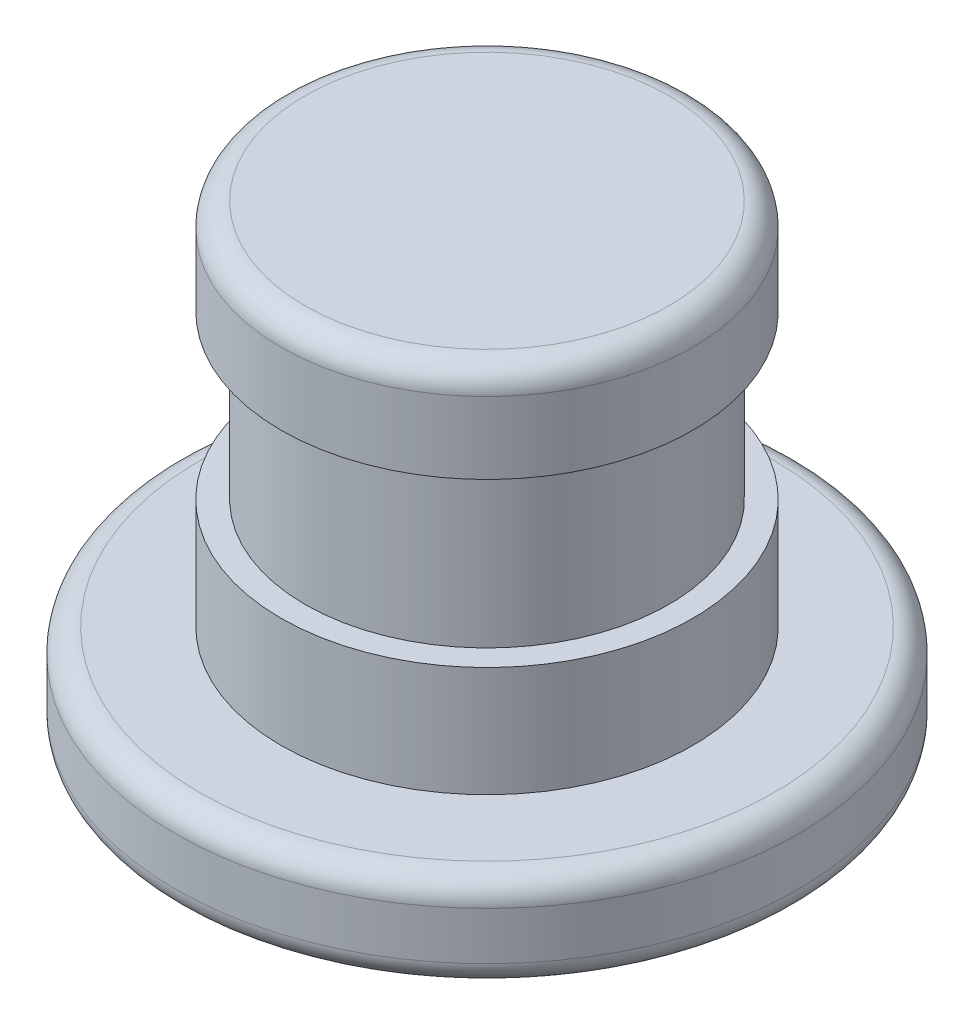
SolidWorks part; units mm, degrees
ref_plane "Plano frontal" through (0, 0, 0) normal (0, 0, 1) x (1, 0, 0)
ref_plane "Plano superior" through (0, 0, 0) normal (0, 1, 0) x (1, 0, 0)
ref_plane "Plano direito" through (0, 0, 0) normal (1, 0, 0) x (0, 0, -1)
sketch "Esboço1" plane through (0, 0, 0) normal (0, 1, 0) x (1, 0, 0)
  circle A0 centre (0, 0) radius 6.5
  dimension "D1" = 13
extrude "Ressalto-extrusão1" add sketch "Esboço1" against normal blind 2
sketch "Esboço2" plane through (0, 0, 0) normal (0, 1, 0) x (1, 0, 0)
  circle A0 centre (0, 0) radius 4.3
  dimension "D1" = 8.6
extrude "Ressalto-extrusão2" add sketch "Esboço2" along normal blind 2.3
sketch "Esboço3" plane through (0, 2.3, 0) normal (0, 1, 0) x (1, 0, 0)
  circle A0 centre (0, 0) radius 3.8
  circle A2 centre (0, 0) radius 4.3 construction
  circle A3 centre (0, 0) radius 4.3 construction
  dimension "D1" = 8.6
  dimension "D2" = 7.6
extrude "Ressalto-extrusão3" add sketch "Esboço3" along normal blind 3.4
sketch "Esboço4" plane through (0, 5.7, 0) normal (0, 1, 0) x (1, 0, 0)
  circle A0 centre (0, 0) radius 4.3 construction
  circle A1 centre (0, 0) radius 4.3
extrude "Ressalto-extrusão4" add sketch "Esboço4" along normal blind 2
fillet "Filete1" radius 0.5 3 edges at (0, 7.7, 4.3) (0, -2, 6.5) (0, 0, 6.5)
equation "\"D2@Esboço3\"=\"D1@Esboço3\"-1"
